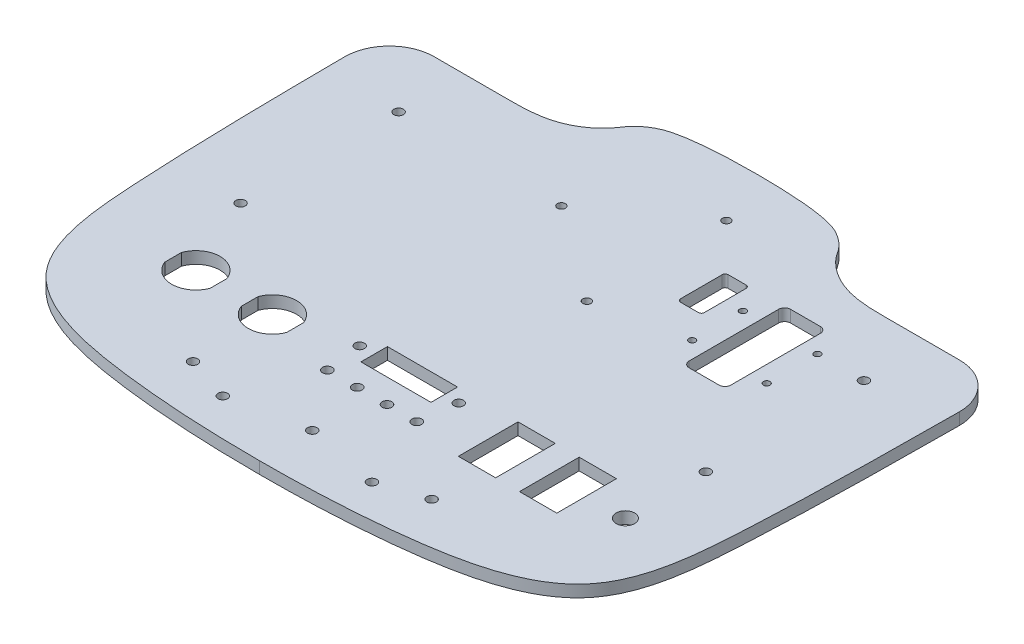
SolidWorks part; units mm, degrees
ref_plane "Front Plane" through (0, 0, 0) normal (0, 0, 1) x (1, 0, 0)
ref_plane "Top Plane" through (0, 0, 0) normal (0, 1, 0) x (1, 0, 0)
ref_plane "Right Plane" through (0, 0, 0) normal (1, 0, 0) x (0, 0, -1)
sketch "Sketch1" plane through (0, 0, 0) normal (0, 1, 0) x (1, 0, 0)
  line L1 (-120, 155) -> (120, 155)
  line L2 (-120, 155) -> (-120, -155)
  line L3 (-120, -155) -> (120, -155)
  line L4 (120, 155) -> (120, -155)
  point P4 (0, 155)
  point P6 (-120, 0)
  dimension "D1" = 240
  dimension "D2" = 310
extrude "Boss-Extrude1" add sketch "Sketch1" along normal blind 4 contours L2 L1 L4 L3
sketch "Sketch2" plane through (0, 4, 0) normal (0, 1, 0) x (1, 0, 0)
  line L0 (-120, 155) -> (120, 155) construction
  line L1 (-120, 0) -> (120, 0)
  line L2 (-120, 155) -> (-120, -155) construction
  circle B0 centre (49, -30) radius 1.75
  circle B1 centre (-49, -30) radius 1.75
  circle B2 centre (-88.957, -132.3382) radius 1.75
  circle B3 centre (0, -146) radius 1.75
  circle B4 centre (88.957, -132.3382) radius 1.75
  circle B5 centre (110.4185, 44.9345) radius 1.75
  circle B6 centre (88.957, 132.3382) radius 1.75
  circle B7 centre (0, 146) radius 1.75
  circle B8 centre (-88.957, 132.3382) radius 1.75
  circle B9 centre (-110.4185, 44.9345) radius 1.75
  spline B10 degree 3 poles (0, 155) (30.5722, 155) (80.3433, 153.7333) (119.2212, 117.6544) (120, 45.41) (120, 0) knots 0 0 0 0 0.458017 0.558017 1 1 1 1
  spline B11 degree 3 poles (0, 155) (-30.5722, 155) (-80.3433, 153.7333) (-119.2212, 117.6544) (-120, 45.41) (-120, 0) knots 0 0 0 0 0.458017 0.558017 1 1 1 1
  spline B12 degree 3 poles (0, -155) (30.5722, -155) (80.3433, -153.7333) (119.2212, -117.6544) (120, -45.41) (120, 0) knots 0 0 0 0 0.458017 0.558017 1 1 1 1
  spline B13 degree 3 poles (0, -155) (-30.5722, -155) (-80.3433, -153.7333) (-119.2212, -117.6544) (-120, -45.41) (-120, 0) knots 0 0 0 0 0.458017 0.558017 1 1 1 1
  line M2 (-120, -155) -> (120, -155)
  line M3 (120, -155) -> (120, 155)
  line M5 (-120, 155) -> (-120, -155)
sketch_block_instance "Base-2-F1-1"
sketch_block "Base-2-F1"
extrude "Cut-Extrude1" cut sketch "Sketch2" against normal up to next contours B13 M2 M5 | B12 M2 M3 | B0 | B2 | B3 | B5
sketch "Sketch3" plane through (0, 4, 0) normal (0, 1, 0) x (1, 0, 0)
  line L5 (-120, 0) -> (120, 0)
  line L6 (-120, 0) -> (-120, 155)
  line L7 (-120, 155) -> (120, 155)
  line L8 (120, 0) -> (120, 155)
  point P4 (0, 0)
  line M23 (120, 0) -> (120, 155)
  line M24 (120, 155) -> (-120, 155)
  line M25 (-120, 155) -> (-120, 0)
  dimension "D1" = 240
  dimension "D2" = 155
extrude "Cut-Extrude2" cut sketch "Sketch3" against normal through all contours L5 M25 M23 M24
sketch "Sketch14" plane through (0, 4, 0) normal (0, 1, 0) x (1, 0, 0)
  line L0 (0, 0) -> (0, -155) construction
  circle A0 centre (78, -75) radius 1.6
  circle A1 centre (78, -22) radius 1.6
  circle A2 centre (40, -128.95) radius 1.6
  circle A3 centre (-40, -128.95) radius 1.6
  circle A4 centre (-78, -75) radius 1.6
  circle A5 centre (-78, -22) radius 1.6
  point P3 (0, -155)
  dimension "D1" = 3.2
  dimension "D2" = 80
  dimension "D3" = 78
  dimension "D4" = 26.05
  dimension "D5" = 40
  dimension "D6" = 53
extrude "Cut-Extrude10" cut sketch "Sketch14" against normal through all
sketch "Sketch16" plane through (0, 4, 0) normal (0, 1, 0) x (1, 0, 0)
  line L0 (0, 0) -> (0, 20) construction
  line L1 (-120, 0) -> (120, 0) construction
  line L2 (-62.5, 0) -> (62.5, 0)
  spline S0 degree 3 poles (-62.5, 0) (-56.8593, 0) (-47.5669, 0.7193) (-37.2478, 7.965) (-35.0117, 13.7063) (-25.1741, 19.0991) (-11.4615, 20) (0, 20) knots 0 0 0 0 0.283629 0.580943 0.775948 0.817853 1 1 1 1
  spline S1 degree 3 poles (62.5, 0) (56.8593, 0) (47.5669, 0.7193) (37.2478, 7.965) (35.0117, 13.7063) (25.1741, 19.0991) (11.4615, 20) (0, 20) knots 0 0 0 0 0.283629 0.580943 0.775948 0.817853 1 1 1 1
  dimension "D1" = 20
  dimension "D2" = 125
extrude "Boss-Extrude3" add sketch "Sketch16" against normal through all
sketch "Sketch17" plane through (0, 4, 0) normal (0, 1, 0) x (1, 0, 0)
  line L0 (103.1101, 0) -> (120, 0)
  line L1 (0, 0) -> (0, -155) construction
  line L2 (62.5, 0) -> (120, 0) construction
  line L3 (-103.1101, 0) -> (-120, 0)
  spline S0 degree 3 poles (0, -146.5903) (13.4599, -146.5903) (46.7542, -145.6395) (97.9604, -134.5675) (102.1242, -80.8714) (102.9233, -39.7469) (103.1101, -11.5683) (103.1101, 0) knots 0 0 0 0 0.214535 0.423704 0.615344 0.849411 1 1 1 1
  spline S1 degree 3 poles (3776.8914, -1471.0236) (-829.8159, 142.6806) (-7.3014, -235.0683) (192.2778, -49.8573) (-118.5349, 1088.9492) (1073.8625, -3883.9573) knots -2.254362 -2.254362 -2.254362 -2.254362 0.458017 0.558017 2.879133 2.879133 2.879133 2.879133 only from (0, -155) to (120, 0) construction
  spline S2 degree 3 poles (0, -155) (30.5722, -155) (80.3433, -153.7333) (119.2212, -117.6544) (120, -45.41) (120, 0) knots 0 0 0 0 0.458017 0.558017 1 1 1 1
  spline S3 degree 3 poles (0, -155) (-30.5722, -155) (-80.3433, -153.7333) (-119.2212, -117.6544) (-120, -45.41) (-120, 0) knots 0 0 0 0 0.458017 0.558017 1 1 1 1
  spline S4 degree 3 poles (0, -146.5903) (-13.4599, -146.5903) (-46.7542, -145.6395) (-97.9604, -134.5675) (-102.1242, -80.8714) (-102.9233, -39.7469) (-103.1101, -11.5683) (-103.1101, 0) knots 0 0 0 0 0.214535 0.423704 0.615344 0.849411 1 1 1 1
extrude "Cut-Extrude11" cut sketch "Sketch17" against normal through all
fillet "Fillet2" radius 15 2 edges at (103.1101, 2, 0) (-103.1101, 2, 0)
sketch "Sketch18" plane through (0, 4, 0) normal (0, 1, 0) x (1, 0, 0)
  line L0 (8.5, 1.4) -> (8.5, -45.4) construction
  line L1 (-23.42, -22) -> (8.5, -22) construction
  circle A0 centre (8.5, 1.4) radius 1.35
  circle A1 centre (8.5, -45.4) radius 1.35
  circle A2 centre (-23.42, -22) radius 1.35
  point P6 (78, -22)
  dimension "D1" = 2.7
  dimension "D2" = 46.8
  dimension "D3" = 31.92
  dimension "D4" = 69.5
  dimension "D5" = 22
extrude "Cut-Extrude12" cut sketch "Sketch18" against normal blind 10
sketch "Sketch19" plane through (0, 4, 0) normal (0, 1, 0) x (1, 0, 0)
  line L0 (8.5, 1.4) -> (8.5, -45.4) construction
  point P5 (78, -22)
  line B0 (40, -10.6) -> (60, -10.6) construction
  line B1 (40, -50.6) -> (60, -50.6) construction
  line B2 (60, -10.6) -> (60, -50.6) construction
  line B3 (60, -30.6) -> (40, -30.6) construction
  line B4 (45, -13.6) -> (55, -13.6)
  line B5 (57, -15.6) -> (57, -45.6)
  line B6 (45, -47.6) -> (55, -47.6)
  line B7 (43, -15.6) -> (43, -45.6)
  circle B8 centre (37.5, -22.1) radius 1.1
  circle B9 centre (37.5, -39.1) radius 1.1
  circle B10 centre (62.5, -39.1) radius 1.1
  circle B11 centre (62.5, -22.1) radius 1.1
  arc B12 (45, -47.6) -> (43, -45.6) centre (45, -45.6) cw
  arc B13 (57, -45.6) -> (55, -47.6) centre (55, -45.6) cw
  arc B14 (55, -13.6) -> (57, -15.6) centre (55, -15.6) cw
  arc B15 (45, -13.6) -> (43, -15.6) centre (45, -15.6) ccw
  dimension "D1" = 18
  dimension "D2" = 12
sketch_block_instance "Block-LD19-USB2Serial-Bracket-1"
sketch_block "Block-LD19-USB2Serial-Bracket" parameters "D5"=2.2, "D6"=2, "D1"=20, "D2"=40, "D3"=22, "D4"=5
extrude "Cut-Extrude13" cut sketch "Sketch19" against normal through all
sketch "Sketch20" plane through (0, 4, 0) normal (0, 1, 0) x (1, 0, 0)
  line L0 (8.5, 1.4) -> (8.5, -45.4) construction
  line L1 (23.5, -14) -> (31.5, -14)
  line L2 (23.5, -14) -> (23.5, -30)
  line L3 (23.5, -30) -> (31.5, -30)
  line L4 (31.5, -14) -> (31.5, -30)
  point P4 (8.5, 1.4)
  point P5 (8.5, -45.4)
  point P10 (23.5, -22)
  point P11 (8.5, -22)
  dimension "D1" = 8
  dimension "D2" = 16
  dimension "D3" = 15
extrude "Cut-Extrude14" cut sketch "Sketch20" against normal through all
fillet "Fillet3" radius 1 4 edges at (31.5, 2, 30) (23.5, 2, 30) (31.5, 2, 14) (23.5, 2, 14)
sketch "Sketch21" plane through (0, 4, 0) normal (0, 1, 0) x (1, 0, 0)
  line L0 (-16.6, -96.45) -> (16.6, -96.45) construction
  line L1 (-11.75, -92) -> (11.75, -92)
  line L2 (-11.75, -92) -> (-11.75, -100.9)
  line L3 (-11.75, -100.9) -> (11.75, -100.9)
  line L4 (11.75, -92) -> (11.75, -100.9)
  circle A0 centre (-16.6, -96.45) radius 1.6
  circle A1 centre (16.6, -96.45) radius 1.6
  point P8 (-11.75, -96.45)
  point P9 (0, -92)
  point P10 (0, -96.45)
  point P12 (-40, -128.95)
  dimension "D4" = 3.2
  dimension "D1" = 23.5
  dimension "D2" = 8.9
  dimension "D3" = 33.2
  dimension "D5" = 92
extrude "Cut-Extrude15" cut sketch "Sketch21" against normal through all
sketch "Sketch22" plane through (0, 4, 0) normal (0, 1, 0) x (1, 0, 0)
  line L0 (32, -101.975) -> (81.1, -101.975) construction
  line L1 (32, -91.975) -> (44.5, -91.975)
  line L2 (32, -91.975) -> (32, -111.975)
  line L3 (32, -111.975) -> (44.5, -111.975)
  line L4 (44.5, -91.975) -> (44.5, -111.975)
  line L5 (52.5, -91.975) -> (65, -91.975)
  line L6 (52.5, -91.975) -> (52.5, -111.975)
  line L7 (52.5, -111.975) -> (65, -111.975)
  line L8 (65, -91.975) -> (65, -111.975)
  line L9 (78, -75) -> (78, -128.95) construction
  line L10 (78, -128.95) -> (40, -128.95) construction
  circle A0 centre (78, -101.975) radius 3.1
  point P10 (44.5, -101.975)
  point P11 (32, -101.975)
  point P12 (52.5, -101.975)
  point P13 (78, -75)
  point P19 (40, -128.95)
  point P24 (78, -101.975)
  dimension "D4" = 6.2
  dimension "D1" = 12.5
  dimension "D2" = 20
  dimension "D3" = 8
  dimension "D5" = 13
extrude "Cut-Extrude16" cut sketch "Sketch22" against normal through all
sketch "Sketch23" plane through (0, 4, 0) normal (0, 1, 0) x (1, 0, 0)
  line L0 (-73.6, -99.1732) -> (-73.6, -104.7768)
  line L1 (-58.4, -99.1732) -> (-58.4, -104.7768)
  line L2 (0, 0) -> (0, -146.5903) construction
  line L7 (-47.95, -99.1732) -> (-47.95, -104.7768)
  line L8 (-32.75, -99.1732) -> (-32.75, -104.7768)
  line L11 (-78, -75) -> (-78, -128.95) construction
  line L12 (-78, -128.95) -> (-40, -128.95) construction
  line L13 (-11.75, -92) -> (-11.75, -100.9) construction
  arc A0 (-73.6, -104.7768) -> (-58.4, -104.7768) centre (-66, -101.975) ccw
  arc A1 (-58.4, -99.1732) -> (-73.6, -99.1732) centre (-66, -101.975) ccw
  arc A2 (-47.95, -104.7768) -> (-32.75, -104.7768) centre (-40.35, -101.975) ccw
  arc A3 (-32.75, -99.1732) -> (-47.95, -99.1732) centre (-40.35, -101.975) ccw
  point P10 (-78, -75)
  point P15 (-40, -128.95)
  point P19 (-78, -101.975)
  dimension "D1" = 16.2
  dimension "D2" = 15.2
  dimension "D3" = 66
  dimension "D4" = 2
  dimension "D5" = 21
extrude "Cut-Extrude17" cut sketch "Sketch23" against normal through all
sketch "Sketch24" plane through (0, 4, 0) normal (0, 1, 0) x (1, 0, 0)
  line L0 (25, -133.95) -> (-25, -133.95) construction
  line L1 (0, -128.95) -> (0, -133.95) construction
  circle A0 centre (-25, -133.95) radius 1.6
  circle A1 centre (25, -133.95) radius 1.6
  circle A2 centre (0, -128.95) radius 1.6
  point P6 (0, 0)
  point P7 (0, -133.95)
  point P11 (-40, -128.95)
  dimension "D1" = 3.2
  dimension "D2" = 50
  dimension "D3" = 5
extrude "Cut-Extrude18" cut sketch "Sketch24" against normal through all
sketch "Sketch25" plane through (0, 4, 0) normal (0, 1, 0) x (1, 0, 0)
  line L0 (-15, -108.9) -> (15, -108.9) construction
  line L1 (-11.75, -100.9) -> (11.75, -100.9) construction
  circle A0 centre (-15, -108.9) radius 1.625
  circle A4 centre (-5, -108.9) radius 1.625
  circle A5 centre (5, -108.9) radius 1.625
  circle A6 centre (15, -108.9) radius 1.625
  point P1 (0, -108.9)
  dimension "D2" = 3.25
  dimension "D1" = 4
  dimension "D3" = 8
extrude "Cut-Extrude19" cut sketch "Sketch25" against normal through all
